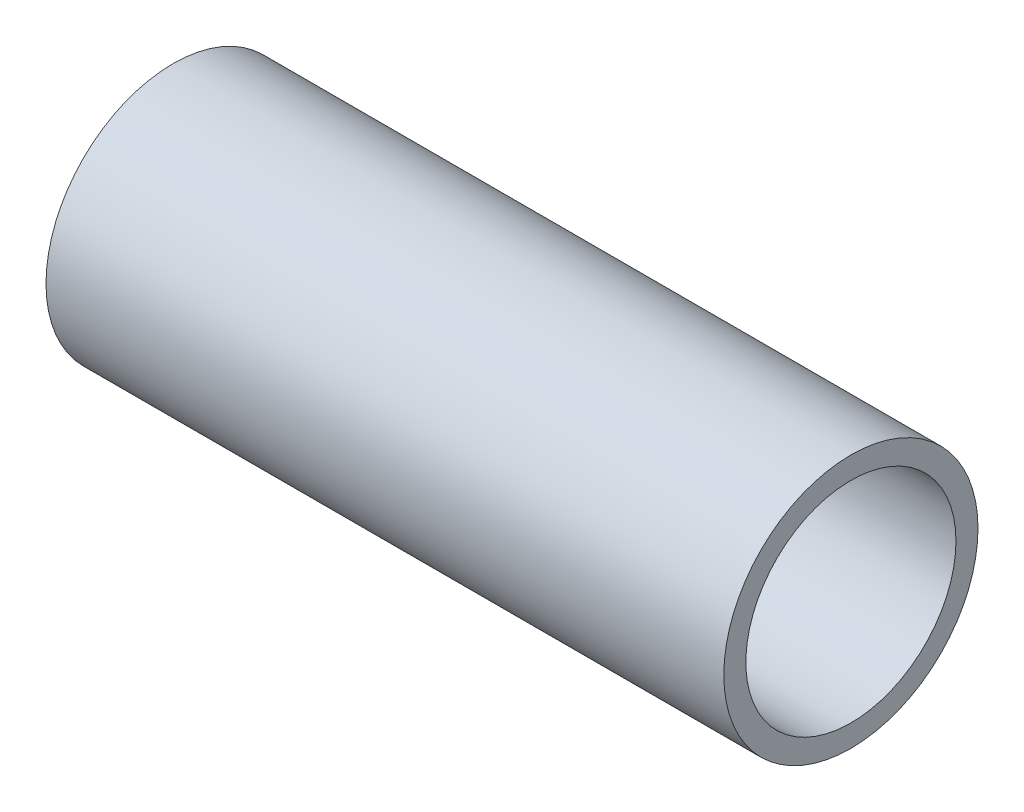
SolidWorks part; units mm, degrees
material "6061-T6 (SS)"
ref_plane "Front Plane" through (0, 0, 0) normal (0, 0, 1) x (1, 0, 0)
ref_plane "Top Plane" through (0, 0, 0) normal (0, 1, 0) x (1, 0, 0)
ref_plane "Right Plane" through (0, 0, 0) normal (1, 0, 0) x (0, 0, -1)
sketch "Sketch1" plane through (0, 0, 0) normal (1, 0, 0) x (0, 0, -1)
  circle A0 centre (0, 0) radius 9.525
  circle A1 centre (0, 0) radius 7.874
  dimension "D1" = 19.05
  dimension "D2" = 15.748
extrude "Boss-Extrude1" add sketch "Sketch1" along normal mid plane 50.8
